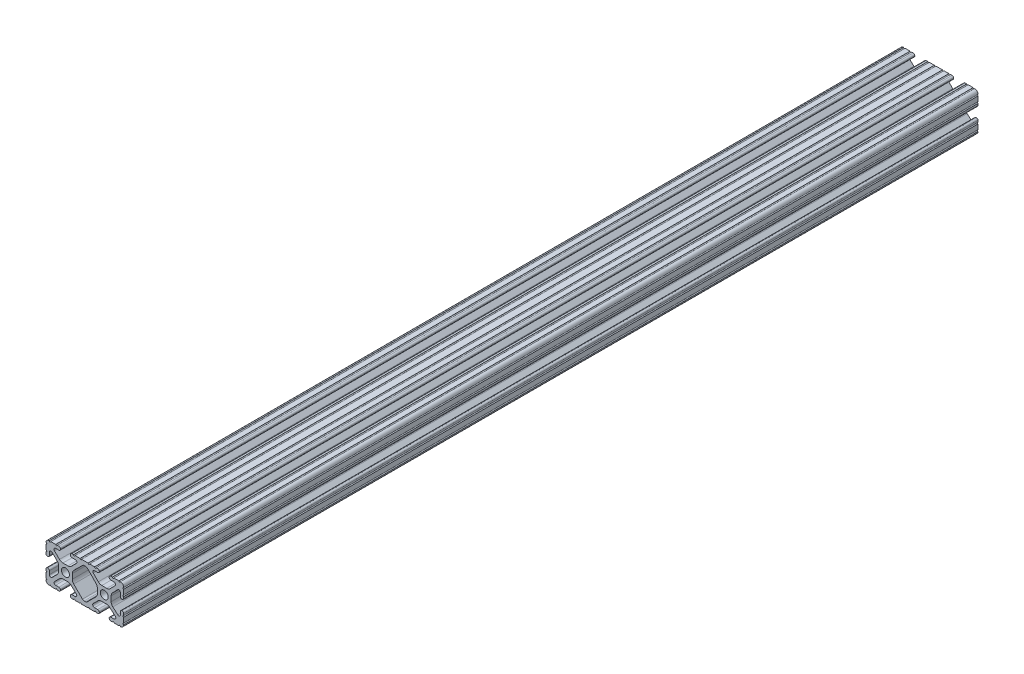
SolidWorks part; units mm, degrees
ref_plane "Front Plane" through (0, 0, 0) normal (0, 0, 1) x (1, 0, 0)
ref_plane "Top Plane" through (0, 0, 0) normal (0, 1, 0) x (1, 0, 0)
ref_plane "Right Plane" through (0, 0, 0) normal (1, 0, 0) x (0, 0, -1)
sketch "Sketch1" plane through (0, 0, 0) normal (0, 0, 1) x (1, 0, 0)
  line L0 (-7.2595, -3.8694) -> (-1.5457, -9.5728)
  line L1 (-8.1915, 1.6223) -> (-8.1915, -1.6223)
  line L2 (-1.504, 9.5765) -> (-7.252, 3.8768)
  line L3 (0.5515, 10.033) -> (-0.3952, 10.033)
  line L4 (7.2829, 3.8459) -> (1.6756, 9.5611)
  line L5 (8.1915, -1.6223) -> (8.1915, 1.6223)
  line L6 (1.5457, -9.5728) -> (7.2595, -3.8694)
  line L7 (-0.4332, -10.033) -> (0.4332, -10.033)
  line L8 (18.0171, 12.7) -> (16.9875, 12.7)
  line L9 (15.9385, 11.651) -> (15.9385, 11.5392)
  line L10 (16.9875, 10.4902) -> (19.1164, 10.4902)
  line L11 (19.8441, 8.7652) -> (16.619, 5.4551)
  line L12 (14.3449, 4.4958) -> (11.0833, 4.4958)
  line L13 (8.817, 5.4472) -> (5.5642, 8.7627)
  line L14 (6.2894, 10.4902) -> (8.4125, 10.4902)
  line L15 (9.4615, 11.5392) -> (9.4615, 11.651)
  line L16 (8.4125, 12.7) -> (7.3829, 12.7)
  line L17 (6.3669, 12.7) -> (3.1496, 12.7)
  line L18 (2.1336, 12.7) -> (-2.1336, 12.7)
  line L19 (-3.1496, 12.7) -> (-6.3669, 12.7)
  line L20 (-7.3829, 12.7) -> (-8.4125, 12.7)
  line L21 (-9.4615, 11.651) -> (-9.4615, 11.5392)
  line L22 (-8.4125, 10.4902) -> (-6.2836, 10.4902)
  line L23 (-5.5326, 8.6661) -> (-8.81, 5.4163)
  line L24 (-11.0455, 4.4958) -> (-14.3545, 4.4958)
  line L25 (-16.59, 5.4163) -> (-19.8674, 8.6661)
  line L26 (-19.1164, 10.4902) -> (-16.9875, 10.4902)
  line L27 (-15.9385, 11.5392) -> (-15.9385, 11.651)
  line L28 (-16.9875, 12.7) -> (-18.0171, 12.7)
  line L29 (-19.0331, 12.7) -> (-22.2504, 12.7)
  line L30 (-25.4, 9.5504) -> (-25.4, 6.3331)
  line L31 (-25.4, 5.3171) -> (-25.4, 4.2375)
  line L32 (-24.401, 3.2385) -> (-24.2392, 3.2385)
  line L33 (-23.1902, 4.2875) -> (-23.1902, 6.3347)
  line L34 (-21.434, 7.0665) -> (-18.148, 3.8082)
  line L35 (-17.2085, 1.5536) -> (-17.2085, -1.6952)
  line L36 (-18.1405, -3.9423) -> (-21.4316, -7.2274)
  line L37 (-23.1902, -6.498) -> (-23.1902, -4.2875)
  line L38 (-24.2392, -3.2385) -> (-24.351, -3.2385)
  line L39 (-25.4, -4.2875) -> (-25.4, -5.3171)
  line L40 (-25.4, -6.3331) -> (-25.4, -9.5504)
  line L41 (-22.2504, -12.7) -> (-19.0331, -12.7)
  line L42 (-18.0171, -12.7) -> (-16.9875, -12.7)
  line L43 (-15.9384, -11.651) -> (-15.9384, -11.5392)
  line L44 (-16.9875, -10.4902) -> (-19.1164, -10.4902)
  line L45 (-19.8341, -8.7551) -> (-16.4966, -5.4237)
  line L46 (-14.2536, -4.4958) -> (-11.1464, -4.4958)
  line L47 (-8.9034, -5.4237) -> (-5.5659, -8.7551)
  line L48 (-6.2836, -10.4902) -> (-8.4125, -10.4902)
  line L49 (-9.4616, -11.5392) -> (-9.4616, -11.651)
  line L50 (-8.4125, -12.7) -> (-7.3829, -12.7)
  line L51 (-6.3669, -12.7) -> (-3.1496, -12.7)
  line L52 (-2.1336, -12.7) -> (2.1336, -12.7)
  line L53 (3.1496, -12.7) -> (6.3669, -12.7)
  line L54 (7.3829, -12.7) -> (8.4125, -12.7)
  line L55 (9.4616, -11.651) -> (9.4616, -11.5392)
  line L56 (8.4125, -10.4902) -> (6.2894, -10.4902)
  line L57 (5.4807, -8.5353) -> (8.5979, -5.4237)
  line L58 (10.8409, -4.4958) -> (14.1026, -4.4958)
  line L59 (16.1879, -5.2766) -> (19.8682, -8.4822)
  line L60 (19.1164, -10.4902) -> (16.9875, -10.4902)
  line L61 (15.9384, -11.5392) -> (15.9384, -11.651)
  line L62 (16.9875, -12.7) -> (18.0171, -12.7)
  line L63 (19.0331, -12.7) -> (22.2504, -12.7)
  line L64 (25.4, -9.5504) -> (25.4, -6.3331)
  line L65 (25.4, -5.3171) -> (25.4, -4.2375)
  line L66 (24.401, -3.2385) -> (24.1892, -3.2385)
  line L67 (23.1902, -4.2375) -> (23.1902, -6.1559)
  line L68 (21.584, -6.8869) -> (18.2982, -4.025)
  line L69 (17.2085, -1.6308) -> (17.2085, 1.6308)
  line L70 (18.1094, 3.8465) -> (21.5263, 7.3534)
  line L71 (23.1902, 6.6769) -> (23.1902, 4.2375)
  line L72 (24.1892, 3.2385) -> (24.401, 3.2385)
  line L73 (25.4, 4.2375) -> (25.4, 5.3171)
  line L74 (25.4, 6.3332) -> (25.4, 9.5504)
  line L75 (22.2504, 12.7) -> (19.0331, 12.7)
  circle A0 centre (-12.7, 0) radius 2.6035
  circle A1 centre (12.7, 0) radius 2.6035
  arc A2 (-1.5457, -9.5728) -> (-0.4332, -10.033) centre (-0.4332, -8.4582) ccw
  arc A3 (-8.1915, -1.6223) -> (-7.2595, -3.8694) centre (-5.0165, -1.6223) ccw
  arc A4 (-7.252, 3.8768) -> (-8.1915, 1.6223) centre (-5.0165, 1.6223) ccw
  arc A5 (-0.3952, 10.033) -> (-1.504, 9.5765) centre (-0.3952, 8.4582) ccw
  arc A6 (1.6756, 9.5611) -> (0.5515, 10.033) centre (0.5515, 8.4582) ccw
  arc A7 (8.1915, 1.6223) -> (7.2829, 3.8459) centre (5.0165, 1.6223) ccw
  arc A8 (7.2595, -3.8694) -> (8.1915, -1.6223) centre (5.0165, -1.6223) ccw
  arc A9 (0.4332, -10.033) -> (1.5457, -9.5728) centre (0.4332, -8.4582) ccw
  arc A10 (18.0171, 12.7) -> (19.0331, 12.7) centre (18.5251, 12.7) ccw
  arc A11 (16.9875, 12.7) -> (15.9385, 11.651) centre (16.9875, 11.651) ccw
  arc A12 (15.9385, 11.5392) -> (16.9875, 10.4902) centre (16.9875, 11.5392) ccw
  arc A13 (19.8441, 8.7652) -> (19.1164, 10.4902) centre (19.1164, 9.4742) ccw
  arc A14 (14.3449, 4.4958) -> (16.619, 5.4551) centre (14.3449, 7.6708) ccw
  arc A15 (8.817, 5.4472) -> (11.0833, 4.4958) centre (11.0833, 7.6708) ccw
  arc A16 (6.2894, 10.4902) -> (5.5642, 8.7627) centre (6.2894, 9.4742) ccw
  arc A17 (8.4125, 10.4902) -> (9.4615, 11.5392) centre (8.4125, 11.5392) ccw
  arc A18 (9.4615, 11.651) -> (8.4125, 12.7) centre (8.4125, 11.651) ccw
  arc A19 (6.3669, 12.7) -> (7.3829, 12.7) centre (6.8749, 12.7) ccw
  arc A20 (2.1336, 12.7) -> (3.1496, 12.7) centre (2.6416, 12.7) ccw
  arc A21 (-3.1496, 12.7) -> (-2.1336, 12.7) centre (-2.6416, 12.7) ccw
  arc A22 (-7.3829, 12.7) -> (-6.3669, 12.7) centre (-6.8749, 12.7) ccw
  arc A23 (-8.4125, 12.7) -> (-9.4615, 11.651) centre (-8.4125, 11.651) ccw
  arc A24 (-9.4615, 11.5392) -> (-8.4125, 10.4902) centre (-8.4125, 11.5392) ccw
  arc A25 (-5.5326, 8.6661) -> (-6.2836, 10.4902) centre (-6.2836, 9.4235) ccw
  arc A26 (-11.0455, 4.4958) -> (-8.81, 5.4163) centre (-11.0455, 7.6708) ccw
  arc A27 (-16.59, 5.4163) -> (-14.3545, 4.4958) centre (-14.3545, 7.6708) ccw
  arc A28 (-19.1164, 10.4902) -> (-19.8674, 8.6661) centre (-19.1164, 9.4235) ccw
  arc A29 (-16.9875, 10.4902) -> (-15.9385, 11.5392) centre (-16.9875, 11.5392) ccw
  arc A30 (-15.9385, 11.651) -> (-16.9875, 12.7) centre (-16.9875, 11.651) ccw
  arc A31 (-19.0331, 12.7) -> (-18.0171, 12.7) centre (-18.5251, 12.7) ccw
  arc A32 (-23.2664, 12.6998) -> (-22.2504, 12.7) centre (-22.7584, 12.7) ccw
  arc A33 (-23.2664, 12.6998) -> (-25.3998, 10.5664) centre (-23.2918, 10.5918) ccw
  arc A34 (-25.4, 9.5504) -> (-25.3998, 10.5664) centre (-25.4, 10.0584) ccw
  arc A35 (-25.4, 5.3171) -> (-25.4, 6.3331) centre (-25.4, 5.8251) ccw
  arc A36 (-25.4, 4.2375) -> (-24.401, 3.2385) centre (-24.401, 4.2375) ccw
  arc A37 (-24.2392, 3.2385) -> (-23.1902, 4.2875) centre (-24.2392, 4.2875) ccw
  arc A38 (-21.434, 7.0665) -> (-23.1902, 6.3347) centre (-22.1596, 6.3347) ccw
  arc A39 (-17.2085, 1.5536) -> (-18.148, 3.8082) centre (-20.3835, 1.5536) ccw
  arc A40 (-18.1405, -3.9423) -> (-17.2085, -1.6952) centre (-20.3835, -1.6952) ccw
  arc A41 (-23.1902, -6.498) -> (-21.4316, -7.2274) centre (-22.1596, -6.498) ccw
  arc A42 (-23.1902, -4.2875) -> (-24.2392, -3.2385) centre (-24.2392, -4.2875) ccw
  arc A43 (-24.351, -3.2385) -> (-25.4, -4.2875) centre (-24.351, -4.2875) ccw
  arc A44 (-25.4, -6.3331) -> (-25.4, -5.3171) centre (-25.4, -5.8251) ccw
  arc A45 (-25.3998, -10.5664) -> (-25.4, -9.5504) centre (-25.4, -10.0584) ccw
  arc A46 (-25.3998, -10.5664) -> (-23.2664, -12.6998) centre (-23.2918, -10.5918) ccw
  arc A47 (-22.2504, -12.7) -> (-23.2664, -12.6998) centre (-22.7584, -12.7) ccw
  arc A48 (-18.0171, -12.7) -> (-19.0331, -12.7) centre (-18.5251, -12.7) ccw
  arc A49 (-16.9875, -12.7) -> (-15.9384, -11.651) centre (-16.9875, -11.651) ccw
  arc A50 (-15.9384, -11.5392) -> (-16.9875, -10.4902) centre (-16.9875, -11.5392) ccw
  arc A51 (-19.8341, -8.7551) -> (-19.1164, -10.4902) centre (-19.1164, -9.4742) ccw
  arc A52 (-14.2536, -4.4958) -> (-16.4966, -5.4237) centre (-14.2536, -7.6708) ccw
  arc A53 (-8.9034, -5.4237) -> (-11.1464, -4.4958) centre (-11.1464, -7.6708) ccw
  arc A54 (-6.2836, -10.4902) -> (-5.5659, -8.7551) centre (-6.2836, -9.4742) ccw
  arc A55 (-8.4125, -10.4902) -> (-9.4616, -11.5392) centre (-8.4125, -11.5392) ccw
  arc A56 (-9.4616, -11.651) -> (-8.4125, -12.7) centre (-8.4125, -11.651) ccw
  arc A57 (-6.3669, -12.7) -> (-7.3829, -12.7) centre (-6.8749, -12.7) ccw
  arc A58 (-2.1336, -12.7) -> (-3.1496, -12.7) centre (-2.6416, -12.7) ccw
  arc A59 (3.1496, -12.7) -> (2.1336, -12.7) centre (2.6416, -12.7) ccw
  arc A60 (7.3829, -12.7) -> (6.3669, -12.7) centre (6.8749, -12.7) ccw
  arc A61 (8.4125, -12.7) -> (9.4616, -11.651) centre (8.4125, -11.651) ccw
  arc A62 (9.4616, -11.5392) -> (8.4125, -10.4902) centre (8.4125, -11.5392) ccw
  arc A63 (5.4807, -8.5353) -> (6.2894, -10.4902) centre (6.2894, -9.3455) ccw
  arc A64 (10.8409, -4.4958) -> (8.5979, -5.4237) centre (10.8409, -7.6708) ccw
  arc A65 (16.1879, -5.2766) -> (14.1026, -4.4958) centre (14.1026, -7.6708) ccw
  arc A66 (19.1164, -10.4902) -> (19.8682, -8.4822) centre (19.1164, -9.3455) ccw
  arc A67 (16.9875, -10.4902) -> (15.9384, -11.5392) centre (16.9875, -11.5392) ccw
  arc A68 (15.9384, -11.651) -> (16.9875, -12.7) centre (16.9875, -11.651) ccw
  arc A69 (19.0331, -12.7) -> (18.0171, -12.7) centre (18.5251, -12.7) ccw
  arc A70 (23.2664, -12.6998) -> (22.2504, -12.7) centre (22.7584, -12.7) ccw
  arc A71 (23.2664, -12.6998) -> (25.3998, -10.5664) centre (23.2918, -10.5918) ccw
  arc A72 (25.4, -9.5504) -> (25.3998, -10.5664) centre (25.4, -10.0584) ccw
  arc A73 (25.4, -5.3171) -> (25.4, -6.3331) centre (25.4, -5.8251) ccw
  arc A74 (25.4, -4.2375) -> (24.401, -3.2385) centre (24.401, -4.2375) ccw
  arc A75 (24.1892, -3.2385) -> (23.1902, -4.2375) centre (24.1892, -4.2375) ccw
  arc A76 (21.584, -6.8869) -> (23.1902, -6.1559) centre (22.2207, -6.1559) ccw
  arc A77 (17.2085, -1.6308) -> (18.2982, -4.025) centre (20.3835, -1.6308) ccw
  arc A78 (18.1094, 3.8465) -> (17.2085, 1.6308) centre (20.3835, 1.6308) ccw
  arc A79 (23.1902, 6.6769) -> (21.5263, 7.3534) centre (22.2207, 6.6769) ccw
  arc A80 (23.1902, 4.2375) -> (24.1892, 3.2385) centre (24.1892, 4.2375) ccw
  arc A81 (24.401, 3.2385) -> (25.4, 4.2375) centre (24.401, 4.2375) ccw
  arc A82 (25.4, 6.3332) -> (25.4, 5.3171) centre (25.4, 5.8251) ccw
  arc A83 (25.3998, 10.5664) -> (25.4, 9.5504) centre (25.4, 10.0584) ccw
  arc A84 (25.3998, 10.5664) -> (23.2664, 12.6998) centre (23.2918, 10.5918) ccw
  arc A85 (22.2504, 12.7) -> (23.2664, 12.6998) centre (22.7584, 12.7) ccw
  point P248 (0, 10.033)
extrude "Boss-Extrude1" add sketch "Sketch1" along normal mid plane 558.8
